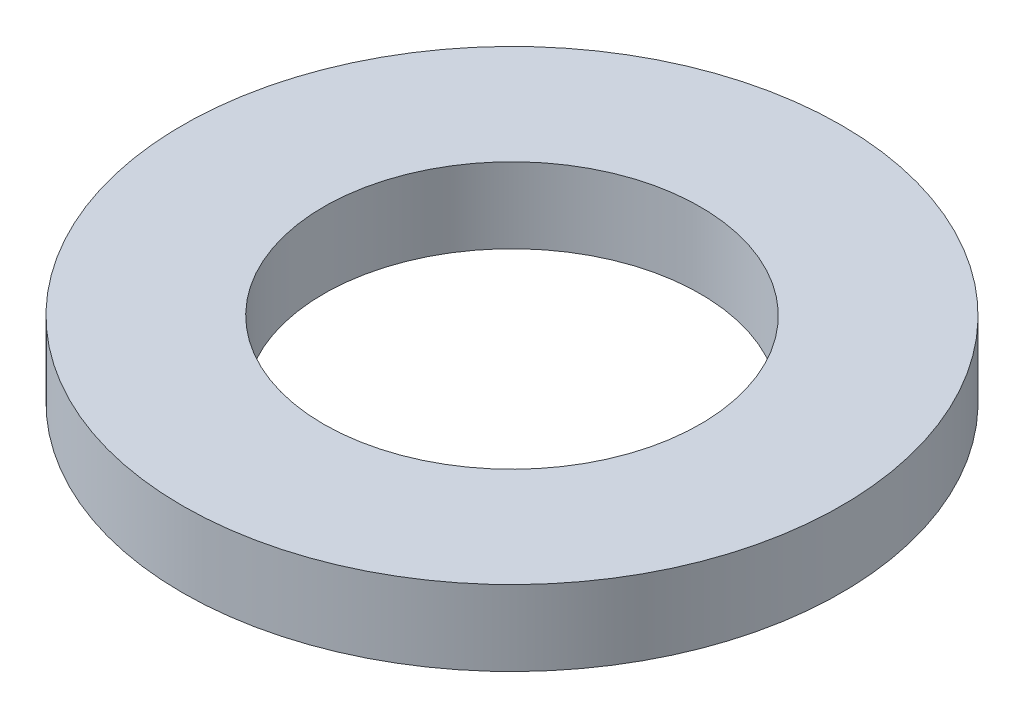
SolidWorks part; units mm, degrees
material "合金钢"
ref_plane "前视基准面" through (0, 0, 0) normal (0, 0, 1) x (1, 0, 0)
ref_plane "上视基准面" through (0, 0, 0) normal (0, 1, 0) x (1, 0, 0)
ref_plane "右视基准面" through (0, 0, 0) normal (1, 0, 0) x (0, 0, -1)
other "Configuration Table"
sketch "草图1" plane through (0, 0, 0) normal (0, 1, 0) x (1, 0, 0)
  circle A0 centre (0, 0) radius 10
  circle A1 centre (0, 0) radius 17.5
  dimension "D1" = 35
  dimension "D2" = 20
extrude "凸台-拉伸1" add sketch "草图1" along normal blind 4
